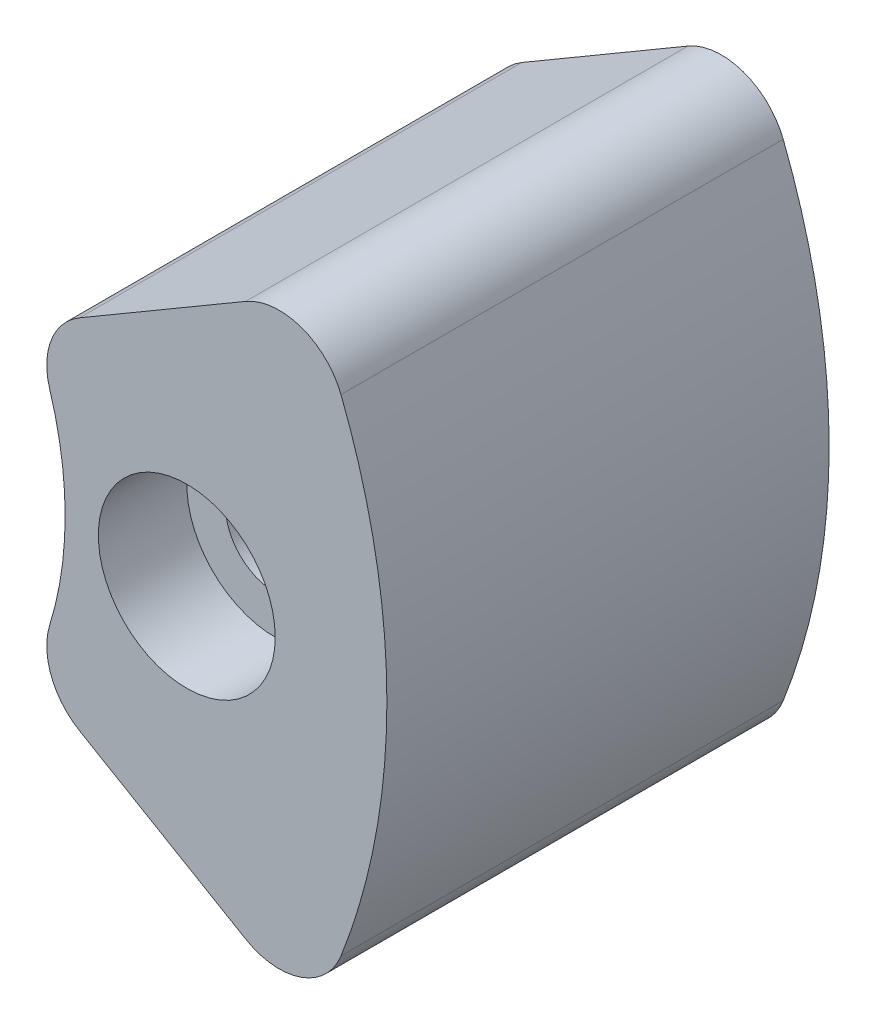
SolidWorks part; units mm, degrees
ref_plane "Front Plane" through (0, 0, 0) normal (0, 0, 1) x (1, 0, 0)
ref_plane "Top Plane" through (0, 0, 0) normal (0, 1, 0) x (1, 0, 0)
ref_plane "Right Plane" through (0, 0, 0) normal (1, 0, 0) x (0, 0, -1)
sketch "Sketch1" plane through (0, 0, 0) normal (0, 0, 1) x (1, 0, 0)
  line L0 (0, 0) -> (30.15, 0) construction
  line L1 (16.2521, 8.0887) -> (23.7645, 12.4887)
  line L2 (16.2521, -8.0887) -> (23.7645, -12.4887)
  arc A0 (14.9024, -4.6129) -> (14.9024, 4.6129) centre (0, 0) ccw
  arc A1 (28.0741, -10.9939) -> (28.0741, 10.9939) centre (0, 0) ccw
  arc A2 (23.7645, 12.4887) -> (28.0741, 10.9939) centre (25.2807, 9.9) cw
  arc A3 (16.2521, 8.0887) -> (14.9024, 4.6129) centre (17.7682, 5.5) ccw
  arc A4 (23.7645, -12.4887) -> (28.0741, -10.9939) centre (25.2807, -9.9) ccw
  arc A5 (16.2521, -8.0887) -> (14.9024, -4.6129) centre (17.7682, -5.5) cw
  point P3 (30.15, 0)
  dimension "D1" = 30.15
  dimension "D2" = 15.6
  dimension "D3" = 3
  dimension "D4" = 5.5
  dimension "D5" = 9.9
extrude "Corpo" add sketch "Sketch1" along normal blind 20
hole_wizard "Rebaixo SHCS M4" positions "Sketch5" profile "Sketch6" counterbore size "M4" standard "ANSI Metric"
sketch "Sketch5" plane through (0, 0, 20) normal (0, 0, 1) x (1, 0, 0)
  line L0 (15.6, 0) -> (30.15, 0) construction
  arc A0 (14.9024, -4.6129) -> (14.9024, 4.6129) centre (0, 0) ccw construction
  arc A1 (28.0741, -10.9939) -> (28.0741, 10.9939) centre (0, 0) ccw construction
  point P0 (21.1, 0)
  point P13 (22.875, 0)
  point P14 (22.875, 0)
  dimension "D1" = 5.5
sketch "Sketch6" plane through (21.1, 0, 20) normal (1, 0, 0) x (0, -1, 0)
  line L0 (0, 0) -> (0, 31.3519)
  line L1 (0, 31.3519) -> (2.25, 30)
  line L2 (2.25, 30) -> (2.25, 4)
  line L3 (2.25, 4) -> (4, 4)
  line L4 (4, 4) -> (4, 0)
  line L5 (4, 0) -> (0, 0)
  line L10 (0, 31.3519) -> (-2.25, 30) construction
  line L11 (0, -6.35) -> (0, 107.95) construction
  dimension "Hole Dia." = 4.5
  dimension "Hole Depth" = 30
  dimension "C'Bore Dia." = 8
  dimension "C'Bore Depth" = 4
  dimension "Drill Angle" = 118
